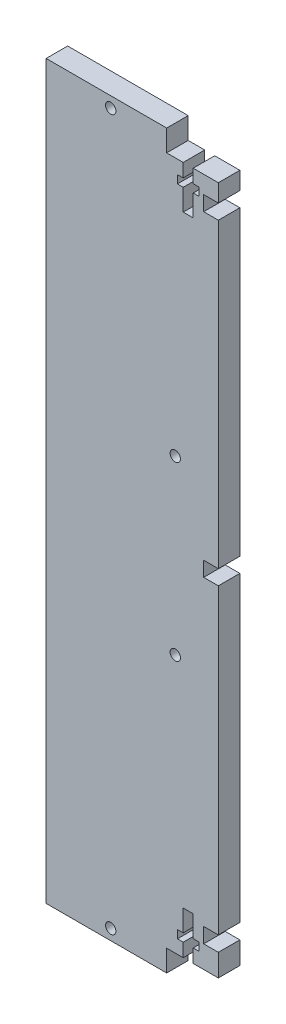
SolidWorks part; units mm, degrees
material "Acrylic (Medium-high impact)"
ref_plane "Front" through (0, 0, 0) normal (0, 0, 1) x (1, 0, 0)
ref_plane "Top" through (0, 0, 0) normal (0, 1, 0) x (1, 0, 0)
ref_plane "Right" through (0, 0, 0) normal (1, 0, 0) x (0, 0, -1)
sketch "Sketch1" plane through (0, 0, 0) normal (0, 0, 1) x (1, 0, 0)
  line L1 (0, 0) -> (152.4, 0)
  line L2 (0, 0) -> (0, 215.9)
  line L3 (0, 215.9) -> (152.4, 215.9)
  line L4 (152.4, 0) -> (152.4, 215.9)
  dimension "D1" = 215.9
  dimension "D2" = 152.4
extrude "Boss-Extrude1" add sketch "Sketch1" along normal blind 6.35
sketch "Sketch2" plane through (0, 0, 6.35) normal (0, 0, 1) x (1, 0, 0)
  line L0 (152.4, 215.9) -> (0, 215.9) construction
  line L1 (133.35, 184.15) -> (133.35, -24.874) construction
  line L2 (152.4, 0) -> (152.4, 215.9) construction
  line L3 (139.0772, 212.725) -> (-50.8887, 212.725) construction
  line L4 (132.7272, 3.175) -> (-102.8916, 3.175) construction
  line L5 (0, 215.9) -> (0, 0) construction
  line L7 (0, 0) -> (152.4, 0) construction
  line L8 (19.05, 212.725) -> (19.05, 66.91) construction
  line L9 (0, 107.95) -> (152.4, 107.95) construction
  line L10 (76.2, 215.9) -> (76.2, 9.0135) construction
  circle A0 centre (19.05, 212.725) radius 1.524
  circle A1 centre (133.35, 212.725) radius 1.524
  circle A2 centre (133.35, 3.175) radius 1.524
  circle A3 centre (19.05, 3.175) radius 1.524
  point P0 (133.35, 212.725)
  point P1 (133.35, 3.175)
  point P2 (19.05, 212.725)
  point P3 (19.05, 3.175)
  point P22 (76.2, 215.9)
  point P26 (0, 107.95)
  dimension "D5" = 3.048
  dimension "D1" = 3.175
  dimension "D2" = 19.05
  dimension "D3" = 19.05
  dimension "D4" = 3.175
extrude "Cut-Extrude1" cut sketch "Sketch2" against normal through all contours A3 | A1
sketch "Sketch4" plane through (0, 0, 6.35) normal (0, 0, 1) x (1, 0, 0)
  line L0 (0, 107.95) -> (183.2199, 107.95) construction
  line L1 (152.4, 0) -> (152.4, 215.9) construction
  line L2 (76.2, 215.9) -> (76.2, 6.5627) construction
  line L4 (0, 215.9) -> (0, 0) construction
  line L5 (152.4, 215.9) -> (0, 215.9) construction
  circle A1 centre (95.25, 133.35) radius 1.524
  circle A3 centre (95.25, 82.55) radius 1.524
  point P6 (0, 107.95)
  point P11 (76.2, 215.9)
  dimension "D1" = 3.048
  dimension "D2" = 57.15
  dimension "D3" = 82.55
extrude "Cut-Extrude2" cut sketch "Sketch4" against normal through all
sketch "Sketch5" plane through (0, 0, 6.35) normal (0, 0, 1) x (1, 0, 0)
  line L0 (0, 107.95) -> (188.4381, 107.95) construction
  line L2 (0, 215.9) -> (0, 0) construction
  line L3 (152.4, 215.9) -> (0, 215.9) construction
  circle A0 centre (38.1, 133.35) radius 1.524
  circle A1 centre (38.1, 82.55) radius 1.524
  point P3 (0, 107.95)
  dimension "D1" = 3.048
  dimension "D2" = 38.1
  dimension "D3" = 82.55
extrude "Cut-Extrude3" cut sketch "Sketch5" against normal through all
sketch "Sketch9" plane through (0, 0, 0) normal (0, 0, -1) x (-1, 0, 0)
  line L0 (-152.4, 215.9) -> (0, 215.9) construction
  line L1 (-116.84, 215.9) -> (-35.56, 215.9)
  line L2 (-116.84, 215.9) -> (-116.84, 209.55)
  line L3 (-116.84, 209.55) -> (-35.56, 209.55)
  line L4 (-35.56, 215.9) -> (-35.56, 209.55)
  line L5 (-14.7626, 107.95) -> (-206.1074, 107.95) construction
  line L6 (0, 215.9) -> (0, 0) construction
  line L7 (-116.84, 6.35) -> (-35.56, 6.35)
  line L8 (-35.56, 0) -> (-35.56, 6.35)
  line L9 (-116.84, 0) -> (-35.56, 0)
  line L10 (-116.84, 0) -> (-116.84, 6.35)
  point P12 (0, 107.95)
  dimension "D1" = 6.35
  dimension "D2" = 16.51
  dimension "D3" = 16.51
extrude "Cut-Extrude9" cut sketch "Sketch9" against normal through all
sketch "Sketch10" plane through (0, 0, 0) normal (0, 0, -1) x (-1, 0, 0)
  line L0 (-35.56, 6.35) -> (-116.84, 6.35) construction
  line L1 (-111.9632, 6.35) -> (-109.0168, 6.35)
  line L2 (-111.9632, 6.35) -> (-111.9632, 10.3187)
  line L3 (-111.9632, 19.05) -> (-109.0168, 19.05)
  line L4 (-109.0168, 6.35) -> (-109.0168, 10.3187)
  line L5 (-113.665, 10.3187) -> (-111.9632, 10.3187)
  line L6 (-113.665, 10.3187) -> (-113.665, 12.7)
  line L7 (-113.665, 12.7) -> (-111.9632, 12.7)
  line L8 (-107.315, 10.3187) -> (-107.315, 12.7)
  line L9 (-111.9632, 6.35) -> (-111.9632, 0) construction
  line L10 (-111.9632, 12.7) -> (-111.9632, 19.05)
  line L11 (-109.0168, 0) -> (-109.0168, 6.35) construction
  line L12 (-109.0168, 12.7) -> (-107.315, 12.7)
  line L13 (-109.0168, 12.7) -> (-109.0168, 19.05)
  line L14 (-109.0168, 10.3187) -> (-107.315, 10.3187)
  line L15 (-2.7493, 107.95) -> (0, 107.95) construction
  line L16 (-76.2, 73.5733) -> (-76.2, 161.5486) construction
  line L17 (-152.4, 0) -> (-152.4, 215.9) construction
  line L18 (-107.315, 205.5813) -> (-107.315, 203.2)
  line L19 (-109.0168, 205.5813) -> (-107.315, 205.5813)
  line L20 (-109.0168, 203.2) -> (-107.315, 203.2)
  line L21 (-109.0168, 203.2) -> (-109.0168, 196.85)
  line L22 (-111.9632, 196.85) -> (-109.0168, 196.85)
  line L23 (-111.9632, 203.2) -> (-111.9632, 196.85)
  line L24 (-113.665, 203.2) -> (-111.9632, 203.2)
  line L25 (-113.665, 205.5813) -> (-111.9632, 205.5813)
  line L26 (-113.665, 205.5813) -> (-113.665, 203.2)
  line L27 (-111.9632, 209.55) -> (-109.0168, 209.55)
  line L28 (-111.9632, 209.55) -> (-111.9632, 205.5813)
  line L29 (-109.0168, 209.55) -> (-109.0168, 205.5813)
  line L30 (-43.3832, 205.5813) -> (-45.085, 205.5813)
  line L31 (-43.3832, 209.55) -> (-43.3832, 205.5813)
  line L32 (-40.4368, 209.55) -> (-43.3832, 209.55)
  line L33 (-40.4368, 209.55) -> (-40.4368, 205.5813)
  line L34 (-38.735, 205.5813) -> (-40.4368, 205.5813)
  line L35 (-38.735, 205.5813) -> (-38.735, 203.2)
  line L36 (-38.735, 203.2) -> (-40.4368, 203.2)
  line L37 (-40.4368, 203.2) -> (-40.4368, 196.85)
  line L38 (-40.4368, 196.85) -> (-43.3832, 196.85)
  line L39 (-43.3832, 203.2) -> (-43.3832, 196.85)
  line L40 (-43.3832, 203.2) -> (-45.085, 203.2)
  line L41 (-45.085, 205.5813) -> (-45.085, 203.2)
  line L42 (-38.735, 10.3187) -> (-38.735, 12.7)
  line L43 (-38.735, 12.7) -> (-40.4368, 12.7)
  line L44 (-40.4368, 12.7) -> (-40.4368, 19.05)
  line L45 (-40.4368, 19.05) -> (-43.3832, 19.05)
  line L46 (-43.3832, 12.7) -> (-43.3832, 19.05)
  line L47 (-43.3832, 12.7) -> (-45.085, 12.7)
  line L48 (-45.085, 10.3187) -> (-45.085, 12.7)
  line L49 (-43.3832, 10.3187) -> (-45.085, 10.3187)
  line L50 (-43.3832, 6.35) -> (-43.3832, 10.3187)
  line L51 (-40.4368, 6.35) -> (-43.3832, 6.35)
  line L52 (-40.4368, 6.35) -> (-40.4368, 10.3187)
  line L53 (-38.735, 10.3187) -> (-40.4368, 10.3187)
  point P23 (-152.4, 107.95)
  point P36 (-76.2, 6.35)
  dimension "D1" = 12.7
  dimension "D2" = 6.35
  dimension "D3" = 2.3813
  dimension "D4" = 6.35
extrude "Cut-Extrude10" cut sketch "Sketch10" against normal through all
sketch "Sketch11" plane through (0, 0, 0) normal (0, 0, -1) x (-1, 0, 0)
  line L1 (-101.6, 209.55) -> (-50.8, 209.55)
  line L2 (-101.6, 209.55) -> (-101.6, 6.35)
  line L3 (-101.6, 6.35) -> (-50.8, 6.35)
  line L4 (-50.8, 209.55) -> (-50.8, 6.35)
extrude "Cut-Extrude11" cut sketch "Sketch11" against normal blind 61.976
sketch "Sketch13" plane through (0, 0, 0) normal (0, 0, -1) x (-1, 0, 0)
  line L0 (-50.8, 6.35) -> (-50.8, 209.55) construction
  line L1 (-46.482, 17.3588) -> (-50.8, 17.3588)
  line L2 (-46.482, 17.3588) -> (-46.482, 12.9198)
  line L3 (-46.482, 12.9198) -> (-50.8, 12.9198)
  line L4 (-50.8, 17.3588) -> (-50.8, 12.9198)
  line L6 (-46.482, 199.9752) -> (-50.8, 199.9752)
  line L7 (-46.482, 199.9752) -> (-46.482, 204.3521)
  line L8 (-46.482, 204.3521) -> (-50.8, 204.3521)
  line L9 (-50.8, 199.9752) -> (-50.8, 204.3521)
  dimension "D1" = 4.318
extrude "Cut-Extrude12" cut sketch "Sketch13" against normal up to next (6.35 mm away)
sketch "Sketch14" plane through (0, 0, 0) normal (0, 0, -1) x (-1, 0, 0)
  line L0 (-50.8, 17.3588) -> (-50.8, 199.9752) construction
  line L1 (-46.482, 106.56) -> (-50.8, 106.56)
  line L2 (-46.482, 106.56) -> (-46.482, 110.9287)
  line L3 (-46.482, 110.9287) -> (-50.8, 110.9287)
  line L4 (-50.8, 106.56) -> (-50.8, 110.9287)
  dimension "D1" = 4.318
extrude "Cut-Extrude13" cut sketch "Sketch14" against normal up to next (6.35 mm away)
sketch "Sketch15" plane through (0, 0, 6.35) normal (0, 0, 1) x (1, 0, 0)
  line L0 (0, 0) -> (35.56, 0) construction
  line L1 (80.4306, 228.6) -> (206.2368, 228.6)
  line L2 (80.4306, 228.6) -> (80.4306, 0)
  line L3 (80.4306, 0) -> (206.2368, 0)
  line L4 (206.2368, 228.6) -> (206.2368, 0)
  line L5 (0, 215.9) -> (0, 0) construction
  dimension "D1" = 80.4306
  dimension "D2" = 125.8061
  dimension "D3" = 228.6
extrude "Getting rid of top, impinges with door" cut sketch "Sketch15" against normal through all
